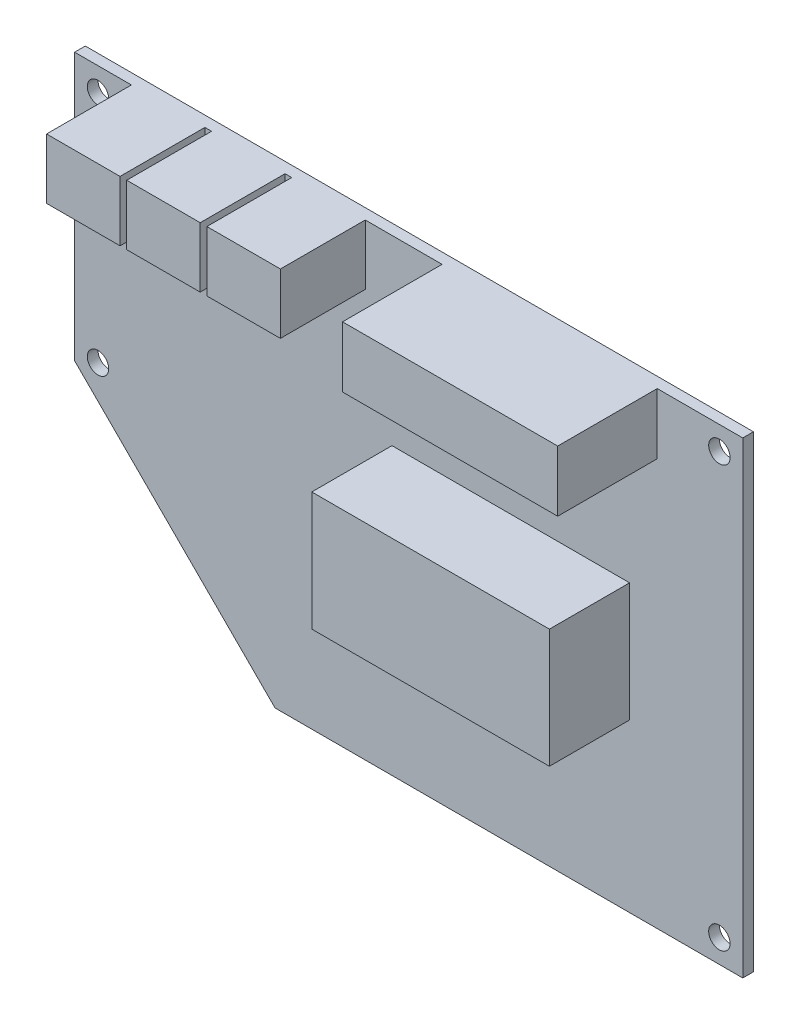
SolidWorks part; units mm, degrees
ref_plane "Plan de face" through (0, 0, 0) normal (0, 0, 1) x (1, 0, 0)
ref_plane "Plan de dessus" through (0, 0, 0) normal (0, 1, 0) x (1, 0, 0)
ref_plane "Plan de droite" through (0, 0, 0) normal (1, 0, 0) x (0, 0, -1)
sketch "Esquisse1" plane through (0, 0, 0) normal (0, 0, 1) x (1, 0, 0)
  line L0 (0, 0) -> (100, 0)
  line L1 (100, 0) -> (100, -70)
  line L2 (100, -70) -> (30, -70)
  line L3 (30, -70) -> (0, -40)
  line L4 (0, -40) -> (0, 0)
  circle A0 centre (3.5, -3.5) radius 1.6
  circle A1 centre (96.5, -3.5) radius 1.6
  circle A2 centre (3.5, -38.5) radius 1.6
  circle A3 centre (96.5, -66.5) radius 1.6
  point P14 (0, 0)
  point P15 (0, 0)
  point P16 (3.5, -32.9832)
  point P17 (0, 0)
  point P18 (3.5, -32.4316)
  dimension "D5" = 3.2
  dimension "D1" = 40
  dimension "D2" = 30
  dimension "D3" = 30
  dimension "D4" = 100
  dimension "D6" = 63
  dimension "D7" = 35
  dimension "D8" = 3.5
  dimension "D9" = 3.5
  dimension "D12" = 93
extrude "Boss.-Extru.1" add sketch "Esquisse1" along normal blind 1.6
sketch "Esquisse2" plane through (0, 0, 1.6) normal (0, 0, 1) x (1, 0, 0)
  line L0 (100, 0) -> (0, 0) construction
  line L1 (8.5, 0) -> (19.5, 0)
  line L2 (8.5, 0) -> (8.5, -9)
  line L3 (8.5, -9) -> (19.5, -9)
  line L4 (19.5, 0) -> (19.5, -9)
  line L15 (0, 0) -> (0, -40) construction
  line L25 (20.5, 0) -> (31.5, 0)
  line L26 (20.5, 0) -> (20.5, -9)
  line L27 (20.5, -9) -> (31.5, -9)
  line L28 (31.5, 0) -> (31.5, -9)
  line L29 (32.5, 0) -> (43.5, 0)
  line L30 (32.5, 0) -> (32.5, -9)
  line L31 (32.5, -9) -> (43.5, -9)
  line L32 (43.5, 0) -> (43.5, -9)
  dimension "D1" = 9
  dimension "D2" = 11
  dimension "D3" = 8.5
  dimension "D4" = 1
  dimension "D5" = 1
extrude "Boss.-Extru.2" add sketch "Esquisse2" along normal blind 12.7
sketch "Esquisse3" plane through (0, 0, 1.6) normal (0, 0, 1) x (1, 0, 0)
  line L5 (100, 0) -> (43.5, 0) construction
  line L6 (55, 0) -> (87.2, 0)
  line L7 (55, 0) -> (55, -9.1)
  line L8 (55, -9.1) -> (87.2, -9.1)
  line L9 (87.2, 0) -> (87.2, -9.1)
  line L10 (0, 0) -> (0, -40) construction
  dimension "D1" = 32.2
  dimension "D2" = 9.1
  dimension "D3" = 55
extrude "Boss.-Extru.3" add sketch "Esquisse3" along normal blind 14.9
sketch "Esquisse4" plane through (0, 0, 1.6) normal (0, 0, 1) x (1, 0, 0)
  line L0 (0, 0) -> (0, -40) construction
  line L1 (47.5, -27.25) -> (83.06, -27.25)
  line L2 (47.5, -27.25) -> (47.5, -45.03)
  line L3 (47.5, -45.03) -> (83.06, -45.03)
  line L4 (83.06, -27.25) -> (83.06, -45.03)
  line L5 (8.5, 0) -> (0, 0) construction
  dimension "D1" = 35.56
  dimension "D2" = 17.78
  dimension "D3" = 47.5
  dimension "D4" = 27.25
extrude "Boss.-Extru.4" add sketch "Esquisse4" along normal blind 12
